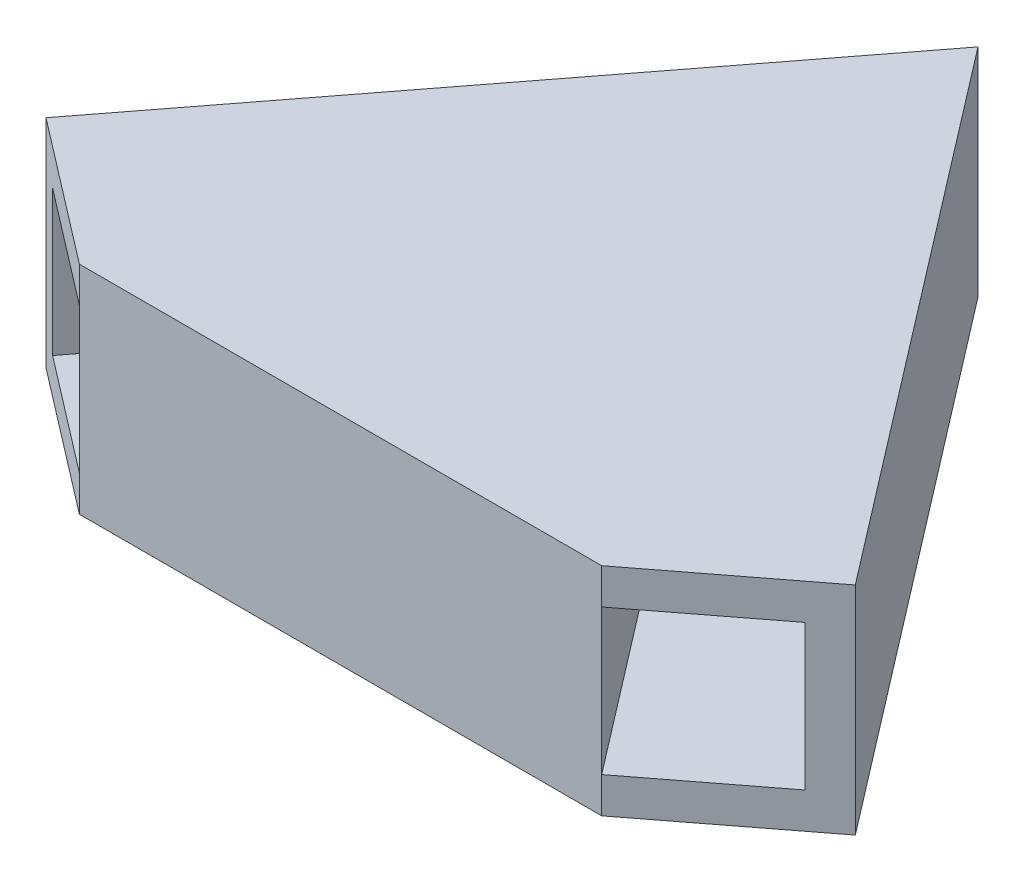
SolidWorks part; units mm, degrees
ref_plane "Front Plane" through (0, 0, 0) normal (0, 0, 1) x (1, 0, 0)
ref_plane "Top Plane" through (0, 0, 0) normal (0, 1, 0) x (1, 0, 0)
ref_plane "Right Plane" through (0, 0, 0) normal (1, 0, 0) x (0, 0, -1)
sketch "Sketch1" plane through (0, 0, 0) normal (0, 1, 0) x (1, 0, 0)
  line L0 (0, 0) -> (-36.5257, -47.6012) construction
  line L1 (0, 0) -> (0, -47.6012) construction
  line L2 (-36.5257, -47.6012) -> (0, -47.6012) construction
  line L3 (-36.5257, -47.6012) -> (-52.6308, -35.2433) construction
  line L4 (0, 0) -> (0, 33.3464) construction
  line L5 (-52.6308, -35.2433) -> (0, 33.3464) construction
  line L6 (-52.6308, -35.2433) -> (-56.5975, -32.1995) construction
  line L7 (0, 33.3464) -> (0, 41.5598) construction
  line L8 (-56.5975, -32.1995) -> (0, 41.5598) construction
  arc A0 (-8.3119, -10.8323) -> (0, -13.6539) centre (0, 0) ccw construction
  point P9 (0, 0)
  point P11 (0, 0)
  point P12 (0, 0)
sketch "Sketch2" plane through (0, 0, 0) normal (0, 1, 0) x (1, 0, 0)
  line L0 (-56.5975, -32.1995) -> (0, 41.5598)
  line L1 (0, 41.5598) -> (0, -47.6012)
  line L2 (0, -47.6012) -> (-36.5257, -47.6012)
  line L3 (-36.5257, -47.6012) -> (-56.5975, -32.1995)
extrude "Boss-Extrude1" add sketch "Sketch2" along normal blind 5
sketch "Sketch4" plane through (0, 5, 0) normal (0, 1, 0) x (1, 0, 0)
  line L0 (-56.5975, -32.1995) -> (-52.6308, -35.2433)
  line L1 (-56.5975, -32.1995) -> (0, 41.5598)
  line L2 (0, 41.5598) -> (0, 33.3464)
  line L3 (0, 33.3464) -> (-52.6308, -35.2433)
extrude "Boss-Extrude2" add sketch "Sketch4" along normal blind 20.3
sketch "Sketch5" plane through (0, 25.3, 0) normal (0, 1, 0) x (1, 0, 0)
  line L0 (-56.5975, -32.1995) -> (-36.5257, -47.6012)
  line L1 (-36.5257, -47.6012) -> (0, -47.6012)
  line L2 (0, -47.6012) -> (0, 41.5598)
  line L3 (0, 41.5598) -> (-56.5975, -32.1995)
extrude "Boss-Extrude3" add sketch "Sketch5" along normal blind 5
sketch "Sketch6" plane through (0, 5, 0) normal (0, 1, 0) x (1, 0, 0)
  line L0 (-36.5257, -47.6012) -> (0, 0) construction
  line L1 (0, -47.6012) -> (0, 33.3464) construction
  line L2 (-52.6308, -35.2433) -> (0, 33.3464) construction
  line L3 (0, 0) -> (-16.1051, 12.3579) construction
  line L4 (0, 0) -> (-2.5, 0) construction
  line L5 (-17.0315, 11.1504) -> (0, -1.9183)
  line L6 (-17.0315, 11.1504) -> (0, 33.3464)
  line L7 (0, -1.9183) -> (0, 33.3464)
extrude "Boss-Extrude4" add sketch "Sketch6" along normal up to surface (20.3 mm away) up to face at (-22.2891, 25.3, 24.2748)
sketch "Sketch7" plane through (0, 5, 0) normal (0, 1, 0) x (1, 0, 0)
  line L0 (-36.5257, -47.6012) -> (-0.9265, -1.2074)
  line L1 (-17.0315, 11.1504) -> (0, -1.9183) construction
  line L2 (0, -1.9183) -> (0, -47.6012)
  line L3 (0, -47.6012) -> (-36.5257, -47.6012)
  line L4 (-0.9265, -1.2074) -> (0, -1.9183)
  point P10 (0, 0)
extrude "Boss-Extrude5" add sketch "Sketch7" along normal up to surface (20.3 mm away) up to face at (-21.2376, 25.3, 24.2427)
mirror "Mirror2" about plane through (0, 5, -41.5598) normal (-1, 0, 0) of "Boss-Extrude5", "Boss-Extrude4", "Boss-Extrude3", "Boss-Extrude2", "Boss-Extrude1"
